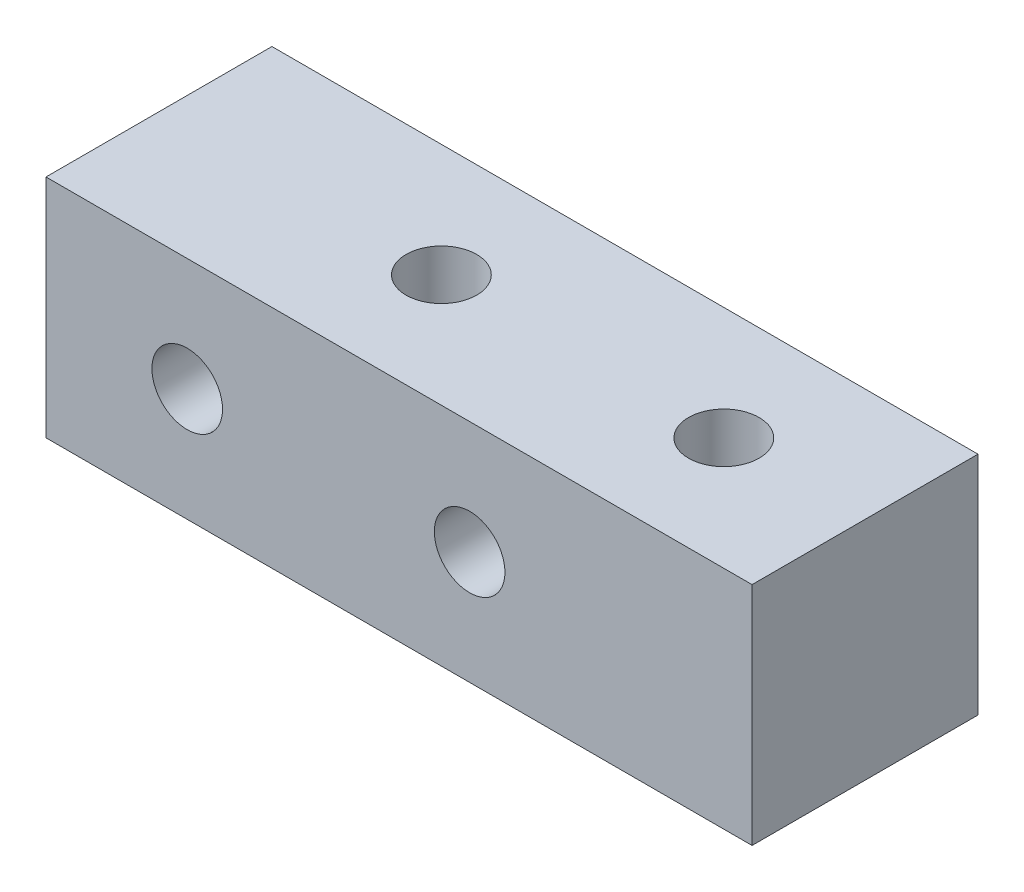
SolidWorks part; units mm, degrees
ref_plane "前视基准面" through (0, 0, 0) normal (0, 0, 1) x (1, 0, 0)
ref_plane "上视基准面" through (0, 0, 0) normal (0, 1, 0) x (1, 0, 0)
ref_plane "右视基准面" through (0, 0, 0) normal (1, 0, 0) x (0, 0, -1)
other "Configuration Table"
sketch "草图1" plane through (0, 0, 0) normal (0, 1, 0) x (1, 0, 0)
  line L1 (-12.5, 4) -> (12.5, 4)
  line L2 (-12.5, 4) -> (-12.5, -4)
  line L3 (-12.5, -4) -> (12.5, -4)
  line L4 (12.5, 4) -> (12.5, -4)
  line L5 (-12.5, 4) -> (12.5, -4) construction
  line L6 (-12.5, -4) -> (12.5, 4) construction
  point P0 (0, 0)
  dimension "D1" = 25
  dimension "D2" = 8
extrude "凸台-拉伸1" add sketch "草图1" along normal blind 8
sketch "草图2" plane through (0, 0, 4) normal (0, 0, 1) x (1, 0, 0)
  line L0 (-12.5, 4) -> (12.5, 4) construction
  line L1 (-12.5, 8) -> (-12.5, 0) construction
  line L2 (12.5, 8) -> (12.5, 0) construction
  point P6 (-7.5, 4)
  point P7 (2.5, 4)
  dimension "D1" = 10
  dimension "D2" = 5
sketch "草图3" plane through (0, 8, 0) normal (0, 1, 0) x (1, 0, 0)
  line L0 (-12.5, 0) -> (12.5, 0) construction
  line L1 (-12.5, 4) -> (-12.5, -4) construction
  line L2 (12.5, -4) -> (12.5, 4) construction
  point P6 (-2.5, 0)
  point P7 (7.5, 0)
  dimension "D1" = 5
  dimension "D2" = 10
hole_wizard "M3 螺纹孔1" positions "草图2" profile "草图4" tap size "M3" standard "GB" end condition through all
sketch "草图4" plane through (2.5, 4, 4) normal (1, 0, 0) x (0, -1, 0)
  line L0 (0, 0) -> (0, 8)
  line L1 (0, 8) -> (1.25, 8)
  line L2 (1.25, 8) -> (1.25, 0)
  line L5 (1.25, 0) -> (0, 0)
  line L11 (0, -6.35) -> (0, 107.95) construction
  dimension "通孔螺纹孔钻头直径" = 2.5
  dimension "通孔螺纹孔钻头深度" = 8
cosmetic thread "孔螺纹线1" parameters "D2"=3
cosmetic thread "孔螺纹线2" parameters "D2"=3
hole_wizard "M3 螺纹孔2" positions "草图3" profile "草图5" tap size "M3" standard "GB" end condition through all
sketch "草图5" plane through (7.5, 8, 0) normal (1, 0, 0) x (0, 0, 1)
  line L0 (0, 0) -> (0, 8)
  line L1 (0, 8) -> (1.25, 8)
  line L2 (1.25, 8) -> (1.25, 0)
  line L5 (1.25, 0) -> (0, 0)
  line L11 (0, -6.35) -> (0, 107.95) construction
  dimension "通孔螺纹孔钻头直径" = 2.5
  dimension "通孔螺纹孔钻头深度" = 8
cosmetic thread "孔螺纹线3" parameters "D2"=3
cosmetic thread "孔螺纹线4" parameters "D2"=3
